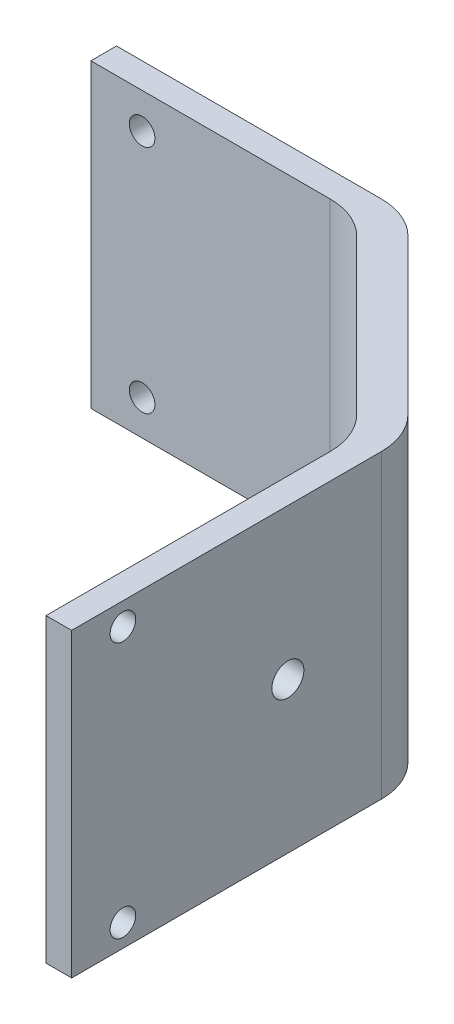
SolidWorks part; units mm, degrees
ref_plane "Front Plane" through (0, 0, 0) normal (0, 0, 1) x (1, 0, 0)
ref_plane "Top Plane" through (0, 0, 0) normal (0, 1, 0) x (1, 0, 0)
ref_plane "Right Plane" through (0, 0, 0) normal (1, 0, 0) x (0, 0, -1)
sketch "Sketch2" plane through (0, 0, 0) normal (0, 0, 1) x (1, 0, 0)
  line L0 (0, 0) -> (71.5, 0)
  line L1 (71.5, 0) -> (71.5, 11)
  line L2 (71.5, 11) -> (0, 11)
  line L3 (0, 11) -> (0, 0)
extrude "Boss-Extrude2" add sketch "Sketch2" along normal blind 4
sketch "Sketch3" plane through (0, 0, 4) normal (0, 0, 1) x (1, 0, 0)
  circle A0 centre (8, 5.5) radius 2
extrude "Cut-Extrude1" cut sketch "Sketch3" against normal blind 4
sketch "Sketch4" plane through (0, 11, 0) normal (0, 1, 0) x (1, 0, 0)
  line L0 (71.5, 0) -> (75.5, 0)
  line L1 (75.5, 0) -> (75.5, -4)
  line L2 (75.5, -4) -> (71.5, -4)
  line L3 (71.5, -4) -> (71.5, 0)
extrude "Boss-Extrude3" add sketch "Sketch4" against normal blind 11
sketch "Sketch5" plane through (0, 0, 4) normal (0, 0, 1) x (1, 0, 0)
  line L0 (75.5, 11) -> (71.5, 11)
  line L1 (75.5, 11) -> (0, 11) construction
  line L2 (71.5, 11) -> (71.5, 0)
  line L3 (0, 0) -> (75.5, 0) construction
  line L4 (71.5, 0) -> (75.5, 0)
  line L5 (75.5, 0) -> (75.5, 11)
extrude "Boss-Extrude4" add sketch "Sketch5" along normal blind 76
sketch "Sketch7" plane through (0, 0, 0) normal (0, 0, -1) x (-1, 0, 0)
  line L0 (-8, 5.5) -> (-8, 41.5)
  line L1 (0, 36) -> (0, 47)
  line L2 (0, 47) -> (-75.5, 47)
  line L3 (-75.5, 47) -> (-75.5, 36)
  line L4 (-75.5, 36) -> (0, 36)
  circle A2 centre (-8, 41.5) radius 2
extrude "Boss-Extrude5" add sketch "Sketch7" against normal up to surface (4 mm away) separate body up to face at (35.75, 5.5, 4)
sketch "Sketch8" plane through (75.5, 0, 0) normal (1, 0, 0) x (0, 0, -1)
  line L0 (0, 47) -> (-80, 47)
  line L1 (-80, 47) -> (-80, 36)
  line L2 (-80, 36) -> (0, 36)
  line L3 (0, 36) -> (0, 47)
extrude "Boss-Extrude8" add sketch "Sketch8" against normal up to surface (4 mm away) up to face at (71.5, 5.5, 42)
sketch "Sketch9" plane through (0, 11, 0) normal (0, 1, 0) x (1, 0, 0)
  line L6 (75.5, 0) -> (0, 0)
  line L7 (0, 0) -> (0, -4)
  line L8 (0, -4) -> (71.5, -4)
  line L9 (71.5, -4) -> (71.5, -80)
  line L10 (71.5, -80) -> (75.5, -80)
  line L11 (75.5, -80) -> (75.5, 0)
  line L12 (75.5, 0) -> (0, 0)
  line L13 (0, 0) -> (0, -4)
  line L14 (0, -4) -> (71.5, -4)
  line L15 (71.5, -4) -> (71.5, -80)
  line L16 (71.5, -80) -> (75.5, -80)
  line L17 (75.5, -80) -> (75.5, 0)
  dimension "D1" = 0
extrude "Boss-Extrude9" add sketch "Sketch9" along normal up to surface (25 mm away) up to face at (49, 36, 28)
sketch "Sketch10" plane through (75.5, 0, 0) normal (1, 0, 0) x (0, 0, -1)
  circle A0 centre (-48.75, 23.5) radius 2.5
extrude "Cut-Extrude3" cut sketch "Sketch10" against normal up to surface (4 mm away) up to face at (71.5, 23.5, 42)
chamfer "Chamfer1" distance 30 angle 45 2 edges at (71.5, 23.5, 4) (75.5, 23.5, 0)
sketch "Sketch13" plane through (75.5, 0, 0) normal (1, 0, 0) x (0, 0, -1)
  line L0 (-48.75, 23.5) -> (-74.5, 23.5)
  line L1 (-74.5, 3.5) -> (-74.5, 43.5)
  circle A0 centre (-74.5, 3.5) radius 2
  circle A1 centre (-74.5, 43.5) radius 2
  point P6 (-74.5, 23.5)
extrude "Cut-Extrude4" cut sketch "Sketch13" against normal up to surface (4 mm away) up to face at (71.5, 23.5, 46.25)
sketch "Sketch14" plane through (75.5, 0, 0) normal (1, 0, 0) x (0, 0, -1)
  line L1 (-82.5, 3.5) -> (-82.5, 47)
  line L2 (-82.5, 47) -> (-80, 47)
  line L3 (-80, 47) -> (-80, 0)
  line L4 (-80, 0) -> (-82.5, 0)
  line L5 (-82.5, 0) -> (-82.5, 3.5)
extrude "Boss-Extrude10" add sketch "Sketch14" against normal up to surface (4 mm away) up to face at (71.5, 43.5, 72.5)
fillet "Fillet1" radius 10 4 edges at (75.5, 23.5, 30) (71.5, 23.5, 34) (41.5, 23.5, 4) (45.5, 23.5, 0)
sketch "Sketch12" plane through (75.5, 0, 0) normal (1, 0, 0) x (0, 0, -1)
  line L0 (-48.75, 23.5) -> (-74.5, 23.5)
